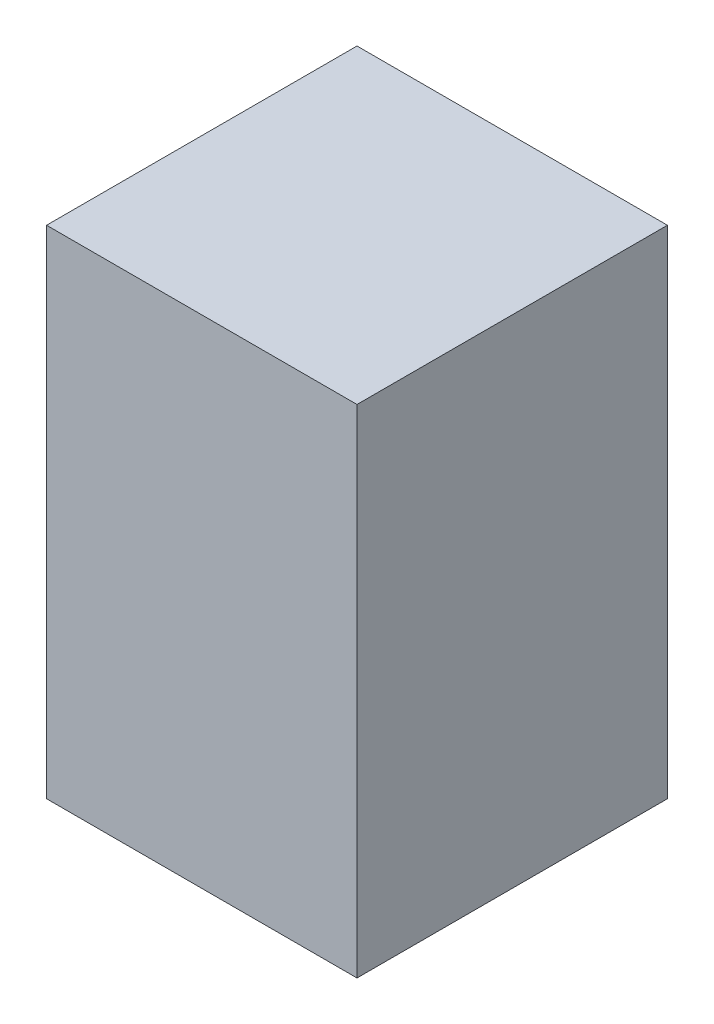
SolidWorks part; units mm, degrees
ref_plane "Front Plane" through (0, 0, 0) normal (0, 0, 1) x (1, 0, 0)
ref_plane "Top Plane" through (0, 0, 0) normal (0, 1, 0) x (1, 0, 0)
ref_plane "Right Plane" through (0, 0, 0) normal (1, 0, 0) x (0, 0, -1)
sketch "Sketch1" plane through (0, 0, 0) normal (0, 0, 1) x (1, 0, 0)
  line L1 (0, 0) -> (500, 0)
  line L2 (0, 0) -> (0, 800)
  line L3 (0, 800) -> (500, 800)
  line L4 (500, 0) -> (500, 800)
  dimension "D1" = 800
  dimension "D2" = 500
extrude "Boss-Extrude1" add sketch "Sketch1" along normal blind 500
